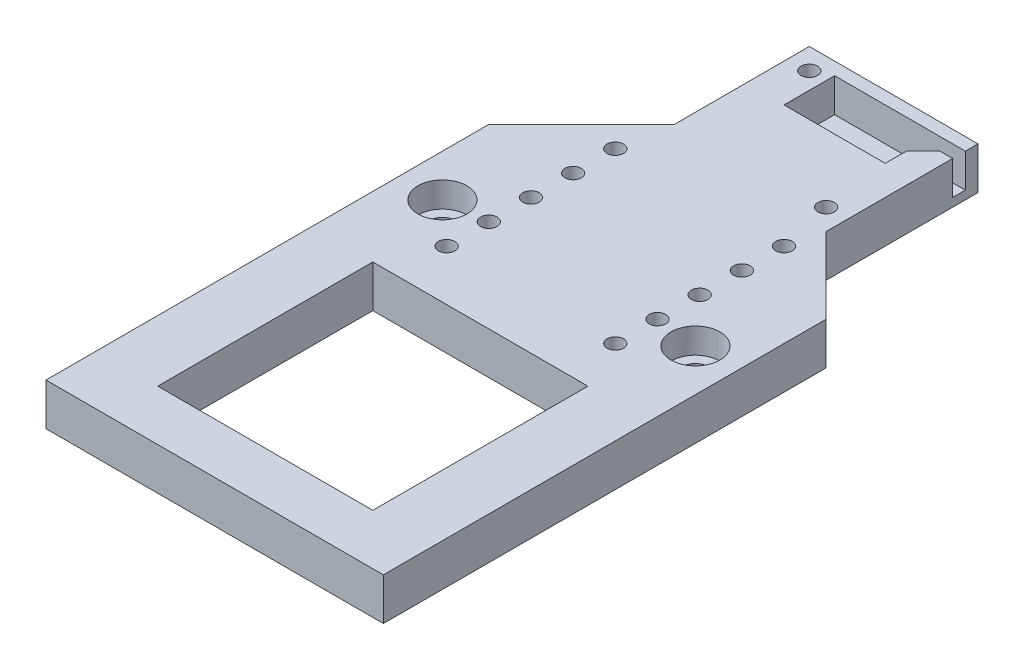
SolidWorks part; units mm, degrees
ref_plane "Front Plane" through (0, 0, 0) normal (0, 0, 1) x (1, 0, 0)
ref_plane "Top Plane" through (0, 0, 0) normal (0, 1, 0) x (1, 0, 0)
ref_plane "Right Plane" through (0, 0, 0) normal (1, 0, 0) x (0, 0, -1)
sketch "Sketch1" plane through (0, 0, 0) normal (0, 1, 0) x (1, 0, 0)
  line L0 (0, 0) -> (0, 22.5) construction
  line L1 (-20, -22.5) -> (20, -22.5)
  line L2 (-20, -22.5) -> (-20, 22.5)
  line L3 (-20, 22.5) -> (20, 22.5)
  line L4 (20, -22.5) -> (20, 22.5)
  line L5 (-20, -22.5) -> (20, 22.5) construction
  line L6 (-20, 22.5) -> (20, -22.5) construction
  line L7 (-15, 15) -> (-15, -15) construction
  line L8 (-15, 15) -> (15, 15) construction
  line L9 (0, 0) -> (-15, 0) construction
  circle A0 centre (-15, 15) radius 1.7
  circle A2 centre (-15, -15) radius 1.7
  circle A3 centre (15, -15) radius 1.7
  circle A5 centre (15, 15) radius 1.7
  point P0 (0, 0)
  dimension "D1" = 3.4
  dimension "D2" = 30
  dimension "D4" = 40
  dimension "D6" = 45
extrude "Boss-Extrude1" add sketch "Sketch1" along normal blind 5
sketch "Sketch7" plane through (0, 5, 0) normal (0, 1, 0) x (1, 0, 0)
  circle A0 centre (-15, 15) radius 2.9
  circle A1 centre (15, 15) radius 2.9
  circle A2 centre (-15, -15) radius 2.9
  circle A3 centre (15, -15) radius 2.9
  dimension "D1" = 5.8
extrude "Cut-Extrude6" cut sketch "Sketch7" against normal offset from surface (3 mm away) 2 up to face at (15, 0, 13.3)
sketch "Sketch4" plane through (0, 5, 0) normal (0, 1, 0) x (1, 0, 0)
  line L0 (11, 13.5) -> (0, 13.5) construction
  line L1 (-6.5, 7) -> (8.5, 7) construction
  line L2 (-6.5, 7) -> (-6.5, 20) construction
  line L3 (-6.5, 20) -> (8.5, 20) construction
  line L4 (8.5, 7) -> (8.5, 20) construction
  line L5 (-6.5, 7) -> (8.5, 20) construction
  line L6 (-6.5, 20) -> (8.5, 7) construction
  line L7 (-9, 4.5) -> (11, 4.5) construction
  line L8 (-9, 4.5) -> (-9, 22.5) construction
  line L9 (-9, 22.5) -> (11, 22.5) construction
  line L10 (11, 4.5) -> (11, 22.5) construction
  line L11 (-9, 4.5) -> (11, 22.5) construction
  line L12 (-9, 22.5) -> (11, 4.5) construction
  line L13 (0, 13.5) -> (0, 0) construction
  line L14 (20, 22.5) -> (-20, 22.5) construction
  circle A0 centre (-6.5, 20) radius 0.975
  circle A2 centre (8.5, 7) radius 0.975
  point P0 (1, 13.5)
  point P9 (1, 13.5)
  dimension "D1" = 1.95
  dimension "D2" = 15
  dimension "D3" = 13
  dimension "D4" = 20
  dimension "D5" = 18
  dimension "D6" = 11
extrude "Cut-Extrude3" cut sketch "Sketch4" against normal through all
sketch "Sketch5" plane through (0, 5, 0) normal (0, 1, 0) x (1, 0, 0)
  line L0 (0, 0) -> (0, -22.5) construction
  line L1 (-20, -22.5) -> (20, -22.5) construction
  circle A0 centre (-10, -19.5) radius 0.975
  circle A1 centre (10, -19.5) radius 0.975
  dimension "D3" = 1.95
  dimension "D1" = 20
  dimension "D2" = 3
extrude "Cut-Extrude4" cut sketch "Sketch5" against normal through all
pattern_linear "LPattern1" count 5 spacing 5 along (0, 0, -1) of "Cut-Extrude4"
sketch "Sketch8" plane through (0, 5, 0) normal (0, 1, 0) x (1, 0, 0)
  line L1 (-4.5, 21) -> (7.5, 21)
  line L2 (-4.5, 21) -> (-4.5, 15)
  line L3 (-4.5, 15) -> (7.5, 15)
  line L4 (7.5, 21) -> (7.5, 15) construction
  line L6 (7.5, 21) -> (15.5, 21)
  line L7 (15.5, 21) -> (15.5, 19.5)
  line L8 (15.5, 19.5) -> (7.5, 19.5)
  line L9 (7.5, 19.5) -> (7.5, 15)
  line L10 (20, 22.5) -> (-20, 22.5) construction
  dimension "D1" = 4.5
  dimension "D2" = 7.5
  dimension "D3" = 6
  dimension "D4" = 8
  dimension "D5" = 1.5
  dimension "D7" = 1.5
extrude "Cut-Extrude7" cut sketch "Sketch8" against normal offset from surface (4 mm away) 1 up to face at (-10, 0, 15.475)
fillet "Fillet2" radius 3 1 edges at (15.5, 1, -20.25)
chamfer "Chamfer2" distance 2 angle 45 1 edges at (7.5, 3, -19.5)
sketch "Sketch9" plane through (0, 5, 0) normal (0, 1, 0) x (1, 0, 0)
  line L0 (-9, 22.5) -> (-9, 6.5)
  line L1 (20, 22.5) -> (-20, 22.5) construction
  line L2 (-9, 6.5) -> (-20, -4.5)
  line L3 (-20, 22.5) -> (-20, -22.5) construction
  line L4 (20, -22.5) -> (20, 22.5) construction
  line L5 (-20, 22.5) -> (-20, -4.5)
  line L6 (20, 22.5) -> (11, 22.5)
  line L7 (20, -4.5) -> (20, 22.5)
  line L8 (-20, -4.5) -> (20, -4.5) construction
  line L9 (0, 0) -> (0, 22.5) construction
  line L10 (11, 4.5) -> (20, -4.5)
  line L11 (11, 22.5) -> (11, 4.5)
  line L12 (-9, 22.5) -> (-20, 22.5)
  line L13 (20, 22.5) -> (-20, 22.5) construction
  dimension "D1" = 9
  dimension "D2" = 45
  dimension "D3" = 11
  dimension "D4" = 45
  dimension "D5" = 18
extrude "Cut-Extrude8" cut sketch "Sketch9" against normal through all
sketch "Sketch10" plane through (0, 5, 0) normal (0, 1, 0) x (1, 0, 0)
  line L1 (-20, -22.5) -> (20, -22.5)
  line L2 (-20, -22.5) -> (-20, -57)
  line L3 (-20, -57) -> (20, -57)
  line L4 (20, -22.5) -> (20, -57)
  line L5 (-12.75, -51) -> (12.75, -51)
  line L6 (-12.75, -51) -> (-12.75, -25.5)
  line L7 (-12.75, -25.5) -> (12.75, -25.5)
  line L8 (0, -22.5) -> (0, -38.25) construction
  line L9 (12.75, -51) -> (12.75, -25.5)
  line L10 (-12.75, -51) -> (12.75, -25.5) construction
  line L11 (-12.75, -25.5) -> (12.75, -51) construction
  dimension "D1" = 25.5
  dimension "D2" = 3
  dimension "D3" = 6
extrude "Boss-Extrude2" add sketch "Sketch10" against normal up to surface (5 mm away) up to face at (0.5, 0, -0.25)
